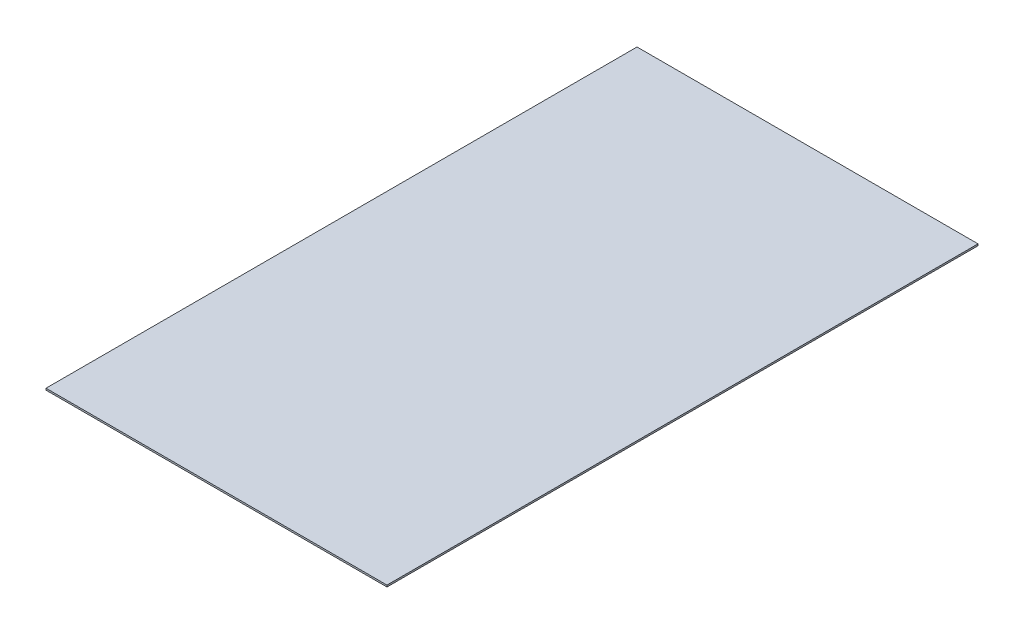
SolidWorks part; units mm, degrees
material "Acrylic (Medium-high impact)"
ref_plane "Front Plane" through (0, 0, 0) normal (0, 0, 1) x (1, 0, 0)
ref_plane "Top Plane" through (0, 0, 0) normal (0, 1, 0) x (1, 0, 0)
ref_plane "Right Plane" through (0, 0, 0) normal (1, 0, 0) x (0, 0, -1)
sketch "Sketch1" plane through (0, 0, 0) normal (0, 1, 0) x (1, 0, 0)
  line L0 (0, -4.2398) -> (0, 81.0142) construction
  line L2 (0, -0.825) -> (0, 0.825) construction
  line L3 (-235.1361, 0) -> (-232.1568, 0) construction
  line L4 (-0.825, 0) -> (0.825, 0) construction
  line L5 (-150, 0) -> (-150, 520)
  line L6 (150, 0) -> (-150, 0)
  line L7 (150, 0) -> (150, 520)
  line L8 (150, 520) -> (-150, 520)
  point P13 (0, 0)
  dimension "D1" = 300
  dimension "D2" = 520
extrude "Boss-Extrude1" add sketch "Sketch1" along normal blind 1.5
